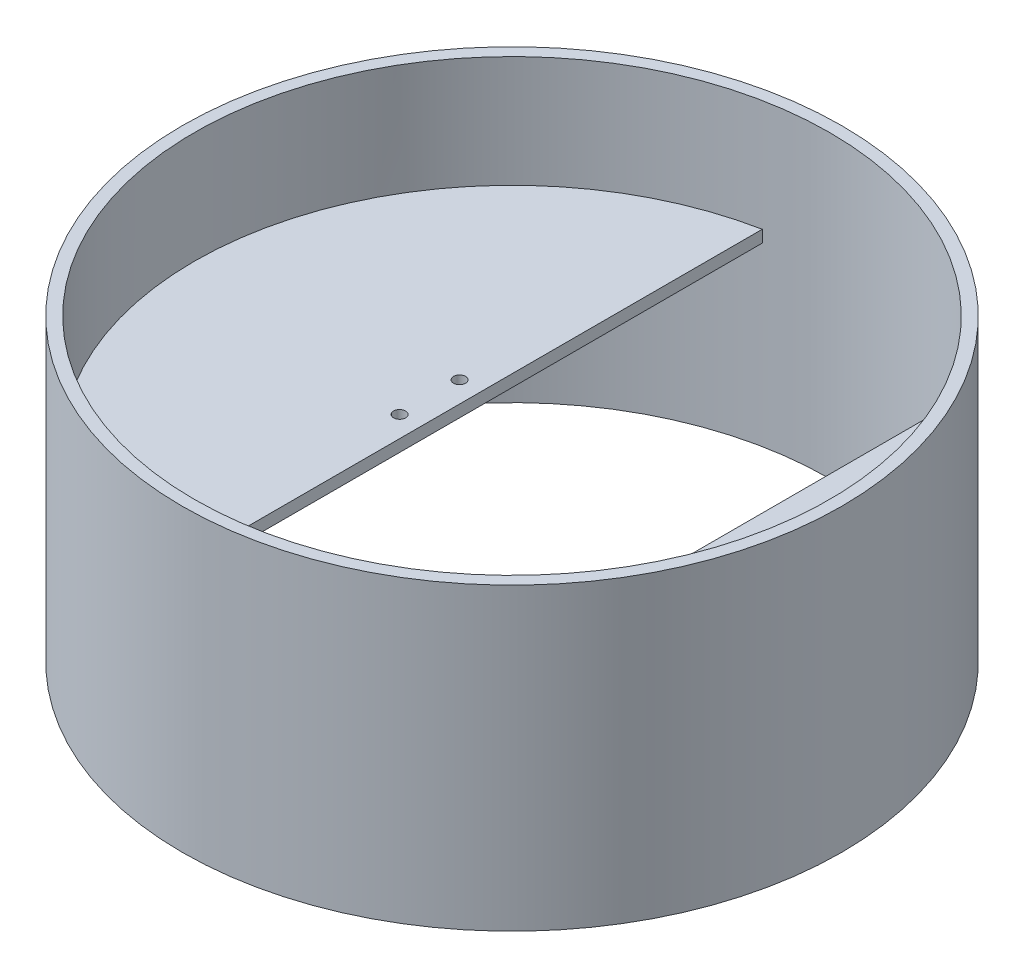
SolidWorks part; units mm, degrees
ref_plane "Front Plane" through (0, 0, 0) normal (0, 0, 1) x (1, 0, 0)
ref_plane "Top Plane" through (0, 0, 0) normal (0, 1, 0) x (1, 0, 0)
ref_plane "Right Plane" through (0, 0, 0) normal (1, 0, 0) x (0, 0, -1)
sketch "Sketch1" plane through (0, 0, 0) normal (0, 1, 0) x (1, 0, 0)
  circle A0 centre (0, 0) radius 55
  circle A1 centre (0, 0) radius 53
  dimension "D1" = 110
  dimension "D2" = 2
extrude "Boss-Extrude1" add sketch "Sketch1" along normal blind 50
ref_plane "Plane1" through (0, 31.4, 0) normal (0, 1, 0) x (1, 0, 0)
sketch "Sketch2" plane through (0, 31.4, 0) normal (0, 1, 0) x (1, 0, 0)
  line L0 (30.75, 43.1676) -> (30.75, -43.1676)
  circle A0 centre (0, 0) radius 53 construction
  dimension "D1" = 30.75
rib "Rib7" sketch "Sketch2" sketch "Sketch2" thickness 2 extrusion direction parallel to sketch draft on no parameters "D1"=2
sketch "Sketch5" plane through (0, 31.4, 0) normal (0, 1, 0) x (1, 0, 0)
  line L0 (-10.25, 51.9994) -> (-10.25, -51.9994)
  line L1 (30.75, 43.1676) -> (30.75, -43.1676) construction
  circle A0 centre (0, 0) radius 53 construction
  dimension "D1" = 41
rib "Rib8" sketch "Sketch5" sketch "Sketch5" thickness 2 extrusion direction parallel to sketch draft on no parameters "D1"=2
sketch "Sketch6" plane through (0, 31.4, 0) normal (0, 1, 0) x (1, 0, 0)
  line L0 (-53, 0) -> (53, 0) construction
  line L1 (-10.25, 51.9994) -> (-10.25, -51.9994) construction
  arc A0 (-10.25, 51.9994) -> (-10.25, -51.9994) centre (0, 0) ccw construction
  arc A1 (30.75, -43.1676) -> (30.75, 43.1676) centre (0, 0) ccw construction
  circle A2 centre (-13.75, -5) radius 1
  circle A3 centre (34.25, -5) radius 1
  circle A4 centre (34.25, 5) radius 1
  circle A5 centre (-13.75, 5) radius 1
  dimension "D1" = 2
  dimension "D2" = 2
  dimension "D6" = 10
  dimension "D3" = 48
  dimension "D4" = 3.5
  dimension "D5" = 5
extrude "Cut-Extrude1" cut sketch "Sketch6" against normal through all
